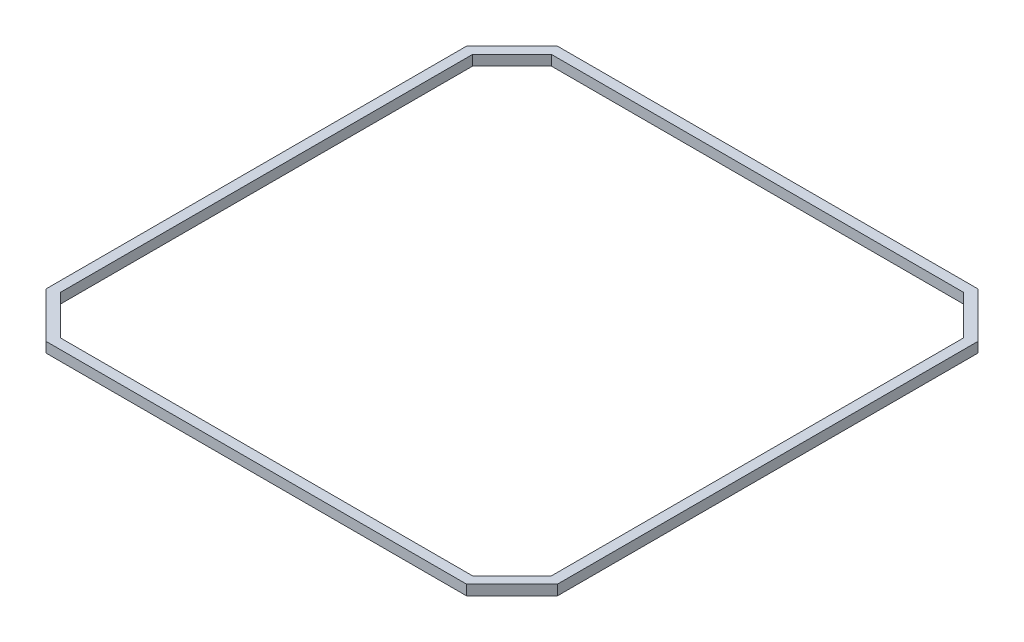
SolidWorks part; units mm, degrees
ref_plane "Front Plane" through (0, 0, 0) normal (0, 0, 1) x (1, 0, 0)
ref_plane "Top Plane" through (0, 0, 0) normal (0, 1, 0) x (1, 0, 0)
ref_plane "Right Plane" through (0, 0, 0) normal (1, 0, 0) x (0, 0, -1)
sketch "Sketch1" plane through (0, 0, 0) normal (0, 1, 0) x (1, 0, 0)
  line L0 (0, 0) -> (0, 45.7586) construction
  line L1 (0, 0) -> (-52.2771, 0) construction
  line L2 (-39.7988, 33.4083) -> (-33.4083, 39.7988)
  line L3 (-33.4083, -39.7988) -> (33.4083, -39.7988)
  line L4 (-39.7988, -33.4083) -> (-39.7988, 33.4083)
  line L5 (-33.4083, 39.7988) -> (33.4083, 39.7988)
  line L6 (39.7988, -33.4083) -> (39.7988, 33.4083)
  line L7 (-39.7988, -39.7988) -> (36.6035, 36.6035) construction
  line L8 (-36.6035, 36.6035) -> (39.7988, -39.7988) construction
  line L9 (33.4083, 39.7988) -> (39.7988, 33.4083)
  line L10 (39.7988, -33.4083) -> (33.4083, -39.7988)
  line L11 (-33.4083, -39.7988) -> (-39.7988, -33.4083)
  line L12 (-41.4488, 34.0917) -> (-34.0917, 41.4488)
  line L13 (34.0917, 41.4488) -> (-34.0917, 41.4488)
  line L14 (34.0917, 41.4488) -> (41.4488, 34.0917)
  line L15 (41.4488, -34.0917) -> (41.4488, 34.0917)
  line L16 (41.4488, -34.0917) -> (34.0917, -41.4488)
  line L17 (-34.0917, -41.4488) -> (34.0917, -41.4488)
  line L18 (-34.0917, -41.4488) -> (-41.4488, -34.0917)
  line L19 (-41.4488, 34.0917) -> (-41.4488, -34.0917)
  point P19 (0, 0)
  point P20 (0, 0)
  point P33 (0, 0)
  dimension "D1" = 1.65
  dimension "D2" = 79.5976
  dimension "D3" = 9.0376
  dimension "D5" = 1.65
  dimension "D6" = 4
  dimension "D4" = 4
extrude "Boss-Extrude1" add sketch "Sketch1" along normal blind 1.65
